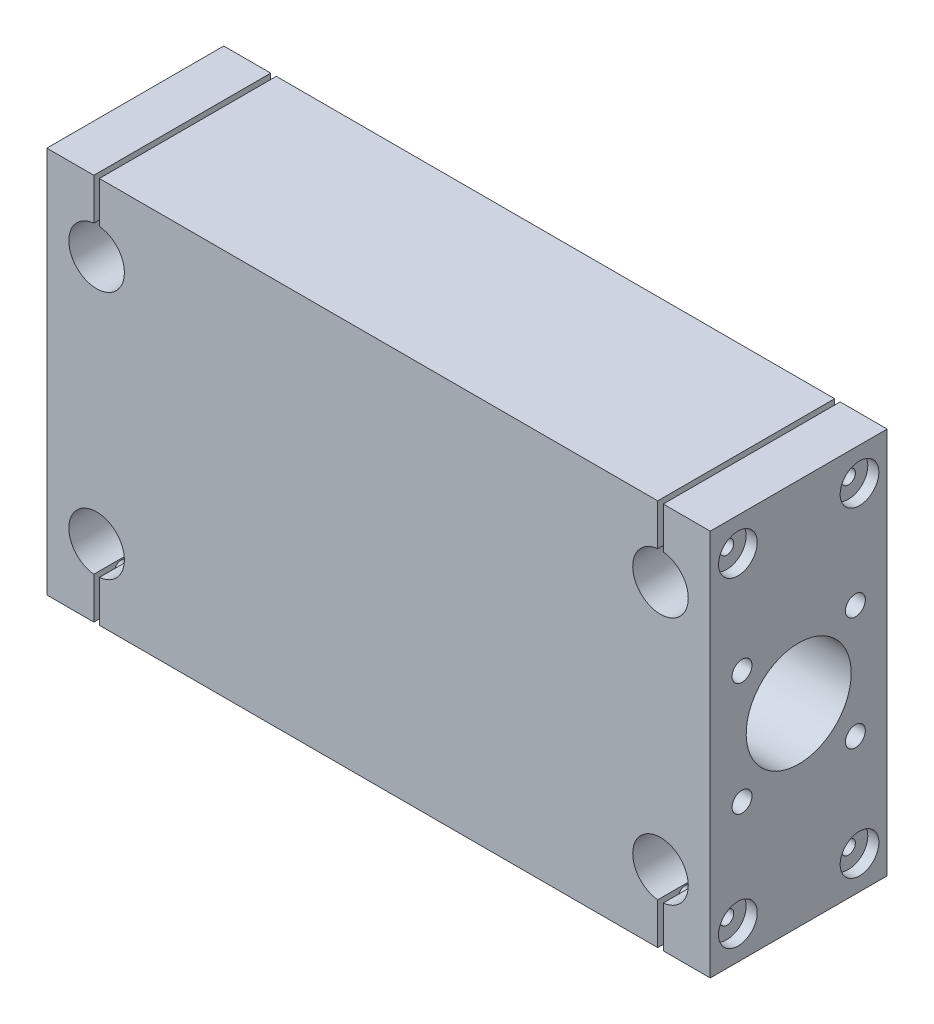
SolidWorks part; units mm, degrees
ref_plane "Front Plane" through (0, 0, 0) normal (0, 0, 1) x (1, 0, 0)
ref_plane "Top Plane" through (0, 0, 0) normal (0, 1, 0) x (1, 0, 0)
ref_plane "Right Plane" through (0, 0, 0) normal (1, 0, 0) x (0, 0, -1)
sketch "Sketch1" plane through (0, 0, 0) normal (0, 0, 1) x (1, 0, 0)
  line L1 (-120, 0) -> (0, 0)
  line L2 (-120, 0) -> (-120, -70)
  line L3 (-120, -70) -> (0, -70)
  line L4 (0, 0) -> (0, -70)
  dimension "D1" = 120
  dimension "D2" = 70
extrude "Boss-Extrude1" add sketch "Sketch1" along normal blind 32
sketch "Sketch2" plane through (-120, 0, 0) normal (-1, 0, 0) x (0, 0, 1)
  line L0 (16, 0) -> (16, -70) construction
  line L1 (32, 0) -> (0, 0) construction
  line L2 (32, -70) -> (0, -70) construction
  line L3 (0, -35) -> (32, -35) construction
  line L4 (0, 0) -> (0, -70) construction
  line L5 (32, 0) -> (32, -70) construction
  circle A0 centre (16, -35) radius 9.5
  dimension "D1" = 19
extrude "Linear_bearing-cut-1" cut sketch "Sketch2" against normal blind 55
sketch "Sketch5" plane through (0, 0, 32) normal (0, 0, 1) x (1, 0, 0)
  line L0 (-60, 0) -> (-60, -70) construction
  line L1 (0, 0) -> (-120, 0) construction
  line L2 (-120, -70) -> (0, -70) construction
  line L3 (0, -35) -> (-120, -35) construction
  line L4 (0, -70) -> (0, 0) construction
  line L5 (-120, 0) -> (-120, -70) construction
  line L6 (-111, 0) -> (-111, -12.5) construction
  line L7 (-111, -12.5) -> (-9, -12.5) construction
  line L8 (-9, -12.5) -> (-9, 0) construction
  line L9 (-9, -57.5) -> (-9, -70) construction
  line L10 (-111, -57.5) -> (-9, -57.5) construction
  line L11 (-111, -70) -> (-111, -57.5) construction
  line L12 (-111.5, 0) -> (-111.5, -7.5)
  line L13 (-110.5, 0) -> (-110.5, -7.5)
  line L14 (-8.5, 0) -> (-8.5, -7.5)
  line L15 (-9.5, 0) -> (-9.5, -7.5)
  line L16 (-111.5, -70) -> (-111.5, -62.5)
  line L17 (-110.5, -70) -> (-110.5, -62.5)
  line L18 (-9.5, -70) -> (-9.5, -62.5)
  line L19 (-8.5, -70) -> (-8.5, -62.5)
  line L20 (-111.5, 0) -> (-110.5, 0)
  line L21 (-9.5, 0) -> (-8.5, 0)
  line L22 (-9.5, -70) -> (-8.5, -70)
  line L23 (-111.5, -70) -> (-110.5, -70)
  arc A0 (-111.5, -7.5) -> (-110.5, -7.5) centre (-111, -12.5) ccw
  arc A1 (-8.5, -7.5) -> (-9.5, -7.5) centre (-9, -12.5) cw
  arc A2 (-111.5, -62.5) -> (-110.5, -62.5) centre (-111, -57.5) cw
  arc A3 (-8.5, -62.5) -> (-9.5, -62.5) centre (-9, -57.5) ccw
  dimension "D1" = 9
  dimension "D3" = 12.5
  dimension "D5" = 0.5
  dimension "D6" = 7.5
extrude "Y-axis-shafts-cut" cut sketch "Sketch5" against normal through all
sketch "Sketch6" plane through (-65, 0, 0) normal (-1, 0, 0) x (0, 0, 1)
  line L0 (16, -25.5) -> (16, -44.5) construction
  circle A0 centre (16, -35) radius 9.5 construction
  circle A1 centre (16, -35) radius 9.5 construction
  circle A2 centre (16, -35) radius 6
  dimension "D1" = 12
sketch "Sketch7" plane through (0, 0, 0) normal (1, 0, 0) x (0, 0, -1)
  circle A0 centre (-16, -35) radius 9.5
  dimension "D1" = 19
extrude "Linear-bearing-cut-2" cut sketch "Sketch7" against normal blind 55
extrude "between-bearings" cut sketch "Sketch6" against normal through all
sketch "Sketch8" plane through (-120, 0, 0) normal (-1, 0, 0) x (0, 0, 1)
  line L0 (5, 0) -> (5, -6) construction
  line L1 (32, 0) -> (0, 0) construction
  line L2 (5, -6) -> (27, -6) construction
  line L3 (27, -6) -> (27, 0) construction
  line L4 (0, 0) -> (0, -70) construction
  line L5 (32, 0) -> (32, -70) construction
  line L6 (16, 0) -> (16, -70) construction
  line L7 (32, -70) -> (0, -70) construction
  line L8 (0, -35) -> (32, -35) construction
  line L9 (5, -39.9148) -> (4.7174, -39.9148) construction
  circle A0 centre (5, -6) radius 3.5
  circle A1 centre (27, -6) radius 3.5
  circle A2 centre (27, -64) radius 3.5
  circle A3 centre (5, -64) radius 3.5
  dimension "D4" = 7
  dimension "D1" = 5
  dimension "D3" = 6
extrude "shaft-holder-screw-cut" cut sketch "Sketch8" against normal blind 4
sketch "Sketch9" plane through (-116, 0, 0) normal (-1, 0, 0) x (0, 0, 1)
  line L0 (5, -2.5) -> (5, -9.5) construction
  line L1 (27, -2.5) -> (27, -9.5) construction
  line L2 (27, -60.5) -> (27, -67.5) construction
  line L3 (5, -60.5) -> (5, -67.5) construction
  circle A0 centre (5, -6) radius 3.5 construction
  circle A1 centre (5, -6) radius 3.5 construction
  circle A2 centre (27, -6) radius 3.5 construction
  circle A3 centre (27, -6) radius 3.5 construction
  circle A4 centre (27, -64) radius 3.5 construction
  circle A5 centre (27, -64) radius 3.5 construction
  circle A6 centre (5, -64) radius 3.5 construction
  circle A7 centre (5, -64) radius 3.5 construction
  circle A8 centre (5, -6) radius 1.25
  circle A9 centre (27, -6) radius 1.25
  circle A10 centre (5, -64) radius 1.25
  circle A11 centre (27, -64) radius 1.25
  dimension "D1" = 2.5
extrude "shaft-holder-screw-cut2" cut sketch "Sketch9" against normal blind 20
sketch "Sketch10" plane through (0, 0, 0) normal (1, 0, 0) x (0, 0, -1)
  line L0 (-27, 0) -> (-27, -6) construction
  line L1 (-32, 0) -> (0, 0) construction
  line L2 (-27, -6) -> (-5, -6) construction
  line L3 (-5, -6) -> (-5, 0) construction
  line L4 (-32, -70) -> (-32, 0) construction
  line L5 (0, -70) -> (0, 0) construction
  line L6 (-16, 0) -> (-16, -70) construction
  line L7 (-32, -70) -> (0, -70) construction
  line L8 (-32, -35) -> (0, -35) construction
  circle A0 centre (-27, -6) radius 3.5
  circle A1 centre (-5, -6) radius 3.5
  circle A2 centre (-5, -64) radius 3.5
  circle A3 centre (-27, -64) radius 3.5
  dimension "D4" = 7
  dimension "D1" = 5
  dimension "D2" = 6
extrude "shaft-holder-screw-cut-3" cut sketch "Sketch10" against normal blind 2
sketch "Sketch11" plane through (-2, 0, 0) normal (1, 0, 0) x (0, 0, -1)
  line L0 (-27, -2.5) -> (-27, -9.5) construction
  line L1 (-5, -2.5) -> (-5, -9.5) construction
  line L2 (-5, -60.5) -> (-5, -67.5) construction
  line L3 (-27, -60.5) -> (-27, -67.5) construction
  circle A0 centre (-27, -6) radius 3.5 construction
  circle A1 centre (-27, -6) radius 3.5 construction
  circle A2 centre (-5, -6) radius 3.5 construction
  circle A3 centre (-5, -6) radius 3.5 construction
  circle A4 centre (-5, -64) radius 3.5 construction
  circle A5 centre (-5, -64) radius 3.5 construction
  circle A6 centre (-27, -64) radius 3.5 construction
  circle A7 centre (-27, -64) radius 3.5 construction
  circle A8 centre (-27, -6) radius 1.25
  circle A9 centre (-5, -6) radius 1.25
  circle A10 centre (-5, -64) radius 1.25
  circle A11 centre (-27, -64) radius 1.25
  dimension "D1" = 2.5
extrude "shaft-holder-screw-cut-4" cut sketch "Sketch11" against normal blind 20
sketch "Sketch12" plane through (0, 0, 0) normal (1, 0, 0) x (0, 0, -1)
  line L0 (-5.75, 0) -> (-5.75, -24.75) construction
  line L1 (-32, 0) -> (0, 0) construction
  line L2 (-5.75, -24.75) -> (0, -24.75) construction
  line L3 (0, -70) -> (0, 0) construction
  line L4 (-16, 0) -> (-16, -70) construction
  line L5 (-32, -70) -> (0, -70) construction
  line L6 (0, -35) -> (-32, -35) construction
  line L7 (-32, -70) -> (-32, 0) construction
  circle A0 centre (-5.75, -24.75) radius 1.8
  circle A1 centre (-26.25, -24.75) radius 1.8
  circle A2 centre (-5.75, -45.25) radius 1.8
  circle A3 centre (-26.25, -45.25) radius 1.8
  dimension "D3" = 3.6
  dimension "D1" = 5.75
  dimension "D2" = 24.75
extrude "Linear-bearing-srew1" cut sketch "Sketch12" against normal blind 14
sketch "Sketch13" plane through (-120, 0, 0) normal (-1, 0, 0) x (0, 0, 1)
  line L0 (27.5, 0) -> (27.5, -24.75) construction
  line L1 (32, 0) -> (0, 0) construction
  line L2 (27.5, -24.75) -> (32, -24.75) construction
  line L3 (32, 0) -> (32, -70) construction
  line L4 (16, 0) -> (16, -70) construction
  line L5 (32, -70) -> (0, -70) construction
  line L6 (32, -35) -> (0, -35) construction
  line L7 (0, 0) -> (0, -70) construction
  circle A0 centre (27.5, -24.75) radius 1.85
  circle A1 centre (4.5, -24.75) radius 1.85
  circle A2 centre (27.5, -45.25) radius 1.85
  circle A3 centre (4.5, -45.25) radius 1.85
  dimension "D3" = 3.7
  dimension "D1" = 24.75
  dimension "D2" = 4.5
extrude "Linear-bearing-screw2" cut sketch "Sketch13" against normal blind 14
